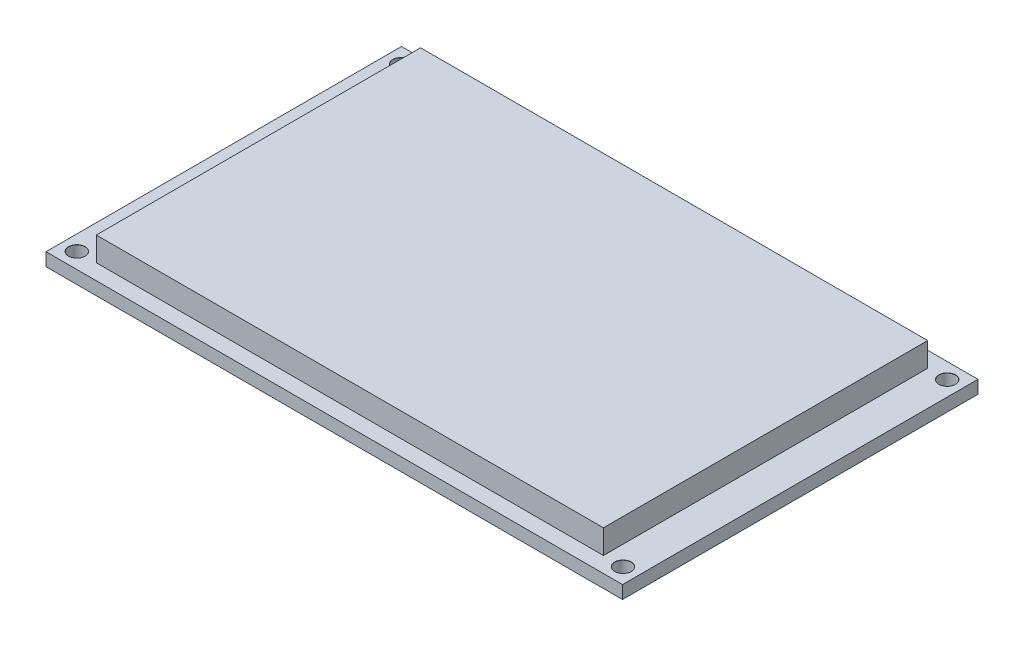
SolidWorks part; units mm, degrees
ref_plane "Front Plane" through (0, 0, 0) normal (0, 0, 1) x (1, 0, 0)
ref_plane "Top Plane" through (0, 0, 0) normal (0, 1, 0) x (1, 0, 0)
ref_plane "Right Plane" through (0, 0, 0) normal (1, 0, 0) x (0, 0, -1)
sketch "Sketch1" plane through (0, 0, 0) normal (0, 1, 0) x (1, 0, 0)
  line L1 (-60, -37) -> (60, -37)
  line L2 (-60, -37) -> (-60, 37)
  line L3 (-60, 37) -> (60, 37)
  line L4 (60, -37) -> (60, 37)
  line L5 (-60, -37) -> (60, 37) construction
  line L6 (-60, 37) -> (60, -37) construction
  point P0 (0, 0)
  dimension "D1" = 74
  dimension "D2" = 120
extrude "Boss-Extrude1" add sketch "Sketch1" along normal blind 2.7
sketch "Sketch2" plane through (0, 2.7, 0) normal (0, 1, 0) x (1, 0, 0)
  line L1 (-52.78, -33.75) -> (52.78, -33.75)
  line L2 (-52.78, -33.75) -> (-52.78, 33.75)
  line L3 (-52.78, 33.75) -> (52.78, 33.75)
  line L4 (52.78, -33.75) -> (52.78, 33.75)
  line L5 (-52.78, -33.75) -> (52.78, 33.75) construction
  line L6 (-52.78, 33.75) -> (52.78, -33.75) construction
  point P0 (0, 0)
  dimension "D1" = 105.56
  dimension "D2" = 67.5
extrude "Boss-Extrude2" add sketch "Sketch2" along normal blind 5
sketch "Sketch3" plane through (0, 2.7, 0) normal (0, 1, 0) x (1, 0, 0)
  line L0 (-56.845, 33.735) -> (56.845, 33.735) construction
  line L1 (56.845, 33.735) -> (56.845, -33.735) construction
  line L2 (56.845, -33.735) -> (-56.845, -33.735) construction
  line L3 (-56.845, -33.735) -> (-56.845, 33.735) construction
  line L4 (-56.845, 0) -> (56.845, 0) construction
  line L5 (60, 37) -> (-60, 37) construction
  line L6 (-60, -37) -> (60, -37) construction
  line L7 (0, 33.735) -> (0, -33.735) construction
  line L8 (-60, 37) -> (-60, -37) construction
  line L9 (60, -37) -> (60, 37) construction
  point P0 (-56.845, 33.735)
  point P1 (-56.845, -33.735)
  point P2 (56.845, -33.735)
  point P3 (56.845, 33.735)
  dimension "D1" = 113.69
  dimension "D2" = 67.47
hole_wizard "M3 Clearance Hole1" positions "Sketch4" profile "Sketch5" hole size "M3" standard "ANSI Metric" end condition through all
sketch "Sketch4" plane through (0, 2.7, 0) normal (0, 1, 0) x (1, 0, 0)
  point P0 (-56.845, 33.735)
  point P3 (56.845, 33.735)
  point P6 (56.845, -33.735)
  point P9 (-56.845, -33.735)
sketch "Sketch5" plane through (-56.845, 2.7, -33.735) normal (1, 0, 0) x (0, 0, 1)
  line L0 (0, 0) -> (0, 2.7)
  line L1 (0, 2.7) -> (1.7, 2.7)
  line L2 (1.7, 2.7) -> (1.7, 0.025)
  line L3 (1.7, 0.025) -> (1.725, 0)
  line L5 (1.725, 0) -> (0, 0)
  line L6 (-1.7, 0.025) -> (-1.725, 0) construction
  line L11 (0, -6.35) -> (0, 107.95) construction
  dimension "Thru Hole Dia." = 3.4
  dimension "Thru Hole Depth" = 2.7
  dimension "Near C'Sink Dia." = 3.45
  dimension "Near C'Sink Angle" = 90
